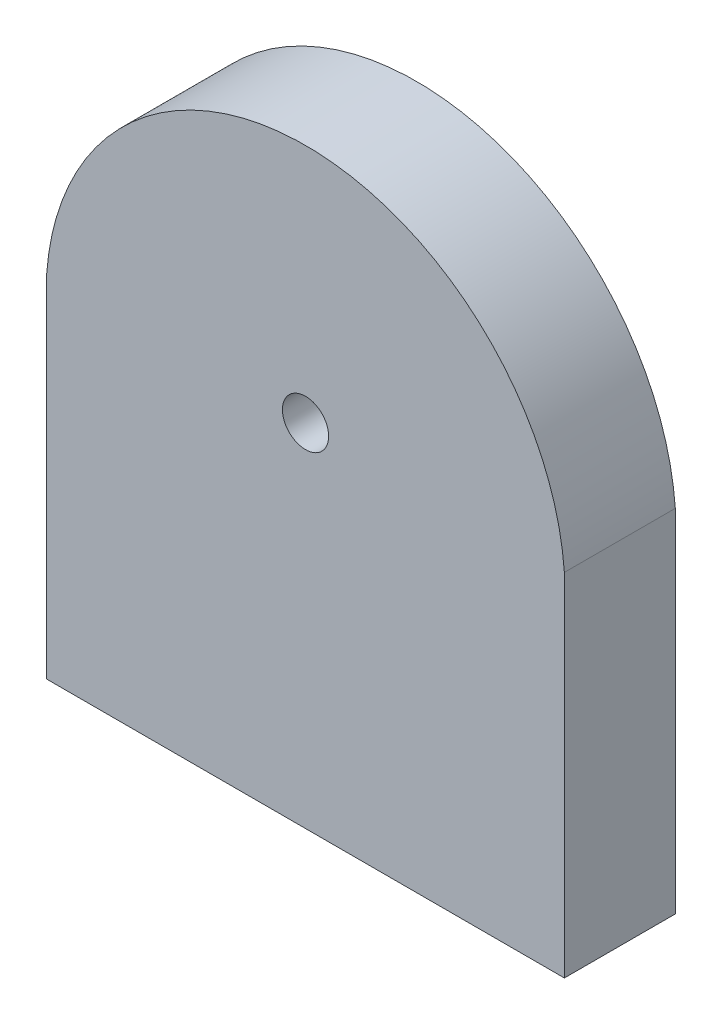
SolidWorks part; units mm, degrees
ref_plane "Front" through (0, 0, 0) normal (0, 0, 1) x (1, 0, 0)
ref_plane "Top" through (0, 0, 0) normal (0, 1, 0) x (1, 0, 0)
ref_plane "Right" through (0, 0, 0) normal (1, 0, 0) x (0, 0, -1)
sketch "Esquisse1" plane through (0, 0, 0) normal (0, 0, 1) x (1, 0, 0)
  line L1 (0, 0) -> (28, 0)
  line L2 (0, 0) -> (0, 32)
  line L3 (0, 32) -> (28, 32)
  line L4 (28, 0) -> (28, 32)
  dimension "D1" = 28
  dimension "D2" = 32
extrude "Boss.-Extru.1" add sketch "Esquisse1" along normal blind 6
sketch "Esquisse2" plane through (0, 0, 0) normal (0, -1, 0) x (1, 0, 0)
  line L0 (0, 3) -> (24.8385, 3) construction
  line L1 (0, 6) -> (0, 0) construction
  line L2 (14, 0) -> (14, 4.923) construction
  line L3 (0, 0) -> (28, 0) construction
  circle A0 centre (6, 3) radius 1.25
  circle A1 centre (22, 3) radius 1.25
  dimension "D1" = 16
  dimension "D2" = 2.5
extrude "Enlèv. mat.-Extru.1" cut sketch "Esquisse2" against normal blind 10
sketch "Esquisse3" plane through (0, 0, 6) normal (0, 0, 1) x (1, 0, 0)
  line L0 (14, 0) -> (14, 19) construction
  line L1 (0, 0) -> (28, 0) construction
  circle A0 centre (14, 19) radius 1.25
  dimension "D1" = 2.5
  dimension "D2" = 19
extrude "Enlèv. mat.-Extru.2" cut sketch "Esquisse3" against normal through all
sketch "Esquisse5" plane through (0, 0, 6) normal (0, 0, 1) x (1, 0, 0)
  line L0 (0, 32) -> (0, 0) construction
  line L1 (28, 0) -> (28, 32) construction
  line L2 (28, 19) -> (0, 19) construction
  line L3 (14, 32) -> (28, 32) construction
  line L4 (0, 19) -> (14, 19) construction
  line L5 (0, 19) -> (0, 33)
  line L6 (0, 33) -> (28, 33)
  line L7 (28, 33) -> (28, 19)
  arc A0 (0, 19) -> (28, 19) centre (14, 17.9615) cw
  dimension "D1" = 1
extrude "Enlèv. mat.-Extru.3" cut sketch "Esquisse5" against normal through all
